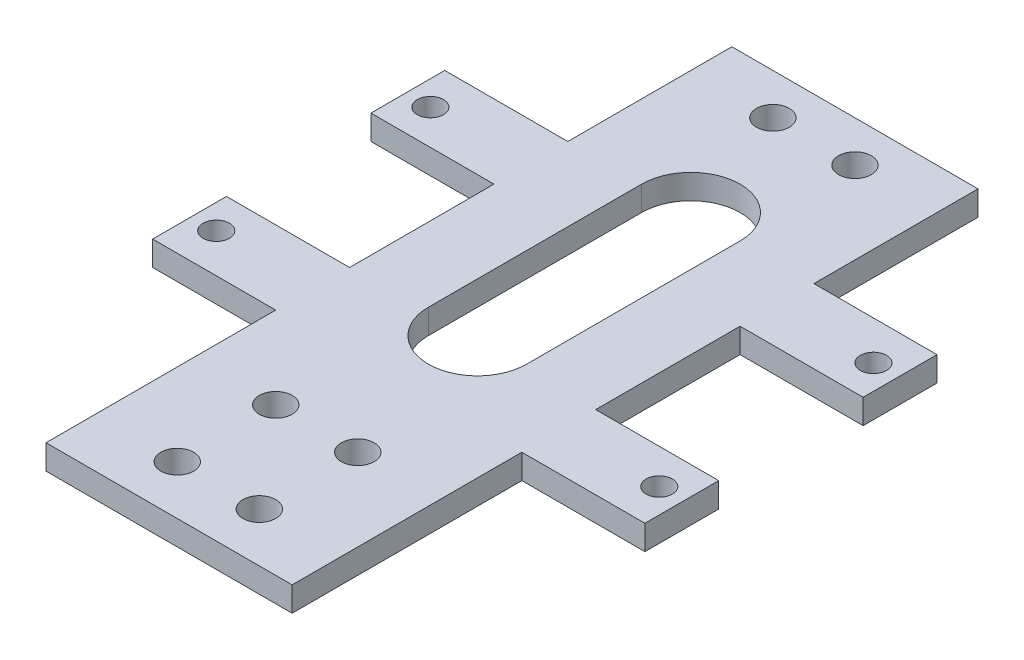
SolidWorks part; units mm, degrees
material "Thornel VCB-20 碳布"
ref_plane "前视基准面" through (0, 0, 0) normal (0, 0, 1) x (1, 0, 0)
ref_plane "上视基准面" through (0, 0, 0) normal (0, 1, 0) x (1, 0, 0)
ref_plane "右视基准面" through (0, 0, 0) normal (1, 0, 0) x (0, 0, -1)
other "Configuration Table"
sketch "草图1" plane through (0, 0, 0) normal (0, 1, 0) x (1, 0, 0)
  line L0 (0, 0) -> (15, 0)
  line L1 (0, 0) -> (60, 0) construction
  line L2 (0, 0) -> (0, 35.6) construction
  line L3 (0, 35.6) -> (60, 35.6) construction
  line L4 (60, 0) -> (60, 35.6) construction
  line L5 (15, 0) -> (15, -28)
  line L6 (0, 0) -> (0, 9)
  line L7 (0, 9) -> (15, 9)
  line L8 (15, 9) -> (15, 26.6)
  line L9 (15, 26.6) -> (0, 26.6)
  line L10 (0, 26.6) -> (0, 35.6)
  line L11 (0, 35.6) -> (15, 35.6)
  line L12 (60, 35.6) -> (60, 26.6)
  line L13 (60, 26.6) -> (45, 26.6)
  line L14 (15, 35.6) -> (15, 55.6)
  line L15 (15, 55.6) -> (45, 55.6)
  line L16 (45, 55.6) -> (45, 35.6)
  line L17 (45, 26.6) -> (45, 9)
  line L18 (45, 9) -> (60, 9)
  line L19 (60, 9) -> (60, 0)
  line L20 (60, 0) -> (45, 0)
  line L21 (45, 0) -> (45, -28)
  line L22 (45, -28) -> (15, -28)
  line L23 (45, 35.6) -> (60, 35.6)
  point P17 (12.3273, 35.6)
  point P22 (0, 0)
  dimension "D1" = 60
  dimension "D2" = 35.6
  dimension "D3" = 9
  dimension "D4" = 30
  dimension "D5" = 28
  dimension "D6" = 20
extrude "凸台-拉伸1" add sketch "草图1" along normal blind 3
sketch "草图2" plane through (0, 3, 0) normal (0, 1, 0) x (1, 0, 0)
  line L0 (0, 0) -> (15, 0) construction
  line L1 (0, 9) -> (0, 0) construction
  line L2 (15, 35.6) -> (0, 35.6) construction
  line L3 (0, 35.6) -> (0, 26.6) construction
  line L4 (60, 35.6) -> (45, 35.6) construction
  line L5 (60, 26.6) -> (60, 35.6) construction
  line L6 (60, 0) -> (60, 9) construction
  line L8 (45, 0) -> (60, 0) construction
  circle A0 centre (3, 4.75) radius 1.6
  circle A1 centre (3, 30.85) radius 1.6
  circle A2 centre (57, 30.85) radius 1.6
  circle A3 centre (57, 4.75) radius 1.6
  point P24 (57.7851, 0)
  dimension "D2" = 3.2
  dimension "D1" = 4.75
  dimension "D3" = 3
  dimension "D4" = 4.75
  dimension "D5" = 3
  dimension "D6" = 4.75
  dimension "D7" = 3
  dimension "D8" = 3
  dimension "D9" = 4.75
extrude "切除-拉伸1" cut sketch "草图2" against normal blind 3
sketch "草图3" plane through (0, 3, 0) normal (0, 1, 0) x (1, 0, 0)
  line L1 (25, 50.6) -> (35, 50.6) construction
  line L2 (25, 50.6) -> (25, -22) construction
  line L3 (25, -22) -> (35, -22) construction
  line L4 (35, 50.6) -> (35, -22) construction
  line L20 (0, 9) -> (0, 0)
  line L21 (0, 0) -> (15, 0)
  line L22 (15, 0) -> (15, -28)
  line L23 (15, -28) -> (45, -28)
  line L24 (45, -28) -> (45, 0)
  line L25 (45, 0) -> (60, 0)
  line L26 (60, 0) -> (60, 9)
  line L27 (60, 9) -> (45, 9)
  line L28 (45, 9) -> (45, 26.6)
  line L29 (45, 26.6) -> (60, 26.6)
  line L30 (60, 26.6) -> (60, 35.6)
  line L31 (60, 35.6) -> (45, 35.6)
  line L32 (45, 35.6) -> (45, 55.6)
  line L33 (45, 55.6) -> (15, 55.6)
  line L34 (15, 55.6) -> (15, 35.6)
  line L35 (15, 35.6) -> (0, 35.6)
  line L36 (0, 35.6) -> (0, 26.6)
  line L37 (0, 26.6) -> (15, 26.6)
  line L38 (15, 26.6) -> (15, 9)
  line L39 (15, 9) -> (0, 9)
  line L40 (0, 9) -> (0, 0) construction
  line L41 (0, 0) -> (15, 0) construction
  line L42 (15, 0) -> (15, -28) construction
  line L43 (15, -28) -> (45, -28) construction
  line L44 (45, -28) -> (45, 0) construction
  line L45 (45, 0) -> (60, 0) construction
  line L46 (60, 0) -> (60, 9) construction
  line L47 (60, 9) -> (45, 9) construction
  line L48 (45, 9) -> (45, 26.6) construction
  line L49 (45, 26.6) -> (60, 26.6) construction
  line L50 (60, 26.6) -> (60, 35.6) construction
  line L51 (60, 35.6) -> (45, 35.6) construction
  line L52 (45, 35.6) -> (45, 55.6) construction
  line L53 (45, 55.6) -> (15, 55.6) construction
  line L54 (15, 55.6) -> (15, 35.6) construction
  line L55 (15, 35.6) -> (0, 35.6) construction
  line L56 (0, 35.6) -> (0, 26.6) construction
  line L57 (0, 26.6) -> (15, 26.6) construction
  line L58 (15, 26.6) -> (15, 9) construction
  line L59 (15, 9) -> (0, 9) construction
  circle A0 centre (25, 50.6) radius 2
  circle A1 centre (35, 50.6) radius 2
  circle A4 centre (35, -22) radius 2
  circle A5 centre (25, -22) radius 2
  circle A6 centre (25, -10) radius 2
  circle A7 centre (35, -10) radius 2
  point P14 (25, 50.6)
  point P16 (25, -10)
  dimension "D6" = 4
  dimension "D2" = 10
  dimension "D3" = 10
  dimension "D4" = 5
  dimension "D5" = 6
  dimension "D9" = 12
  dimension "D10" = 12
  dimension "D1" = 0
extrude "切除-拉伸2" cut sketch "草图3" against normal blind 3
sketch "草图4" plane through (0, 3, 0) normal (0, 1, 0) x (1, 0, 0)
  line L0 (30, 35.6) -> (30, 9.6) construction
  line L1 (36, 35.6) -> (36, 9.6)
  line L2 (24, 35.6) -> (24, 9.6)
  line L3 (45, 55.6) -> (15, 55.6) construction
  line L4 (30, 55.6) -> (30, -28) construction
  line L5 (15, -28) -> (45, -28) construction
  arc A0 (36, 35.6) -> (24, 35.6) centre (30, 35.6) ccw
  arc A1 (24, 9.6) -> (36, 9.6) centre (30, 9.6) ccw
  point P2 (30, 22.6)
  point P7 (30, 37.2087)
  dimension "D2" = 6
  dimension "D1" = 26
  dimension "D3" = 20
extrude "切除-拉伸3" cut sketch "草图4" against normal blind 3
